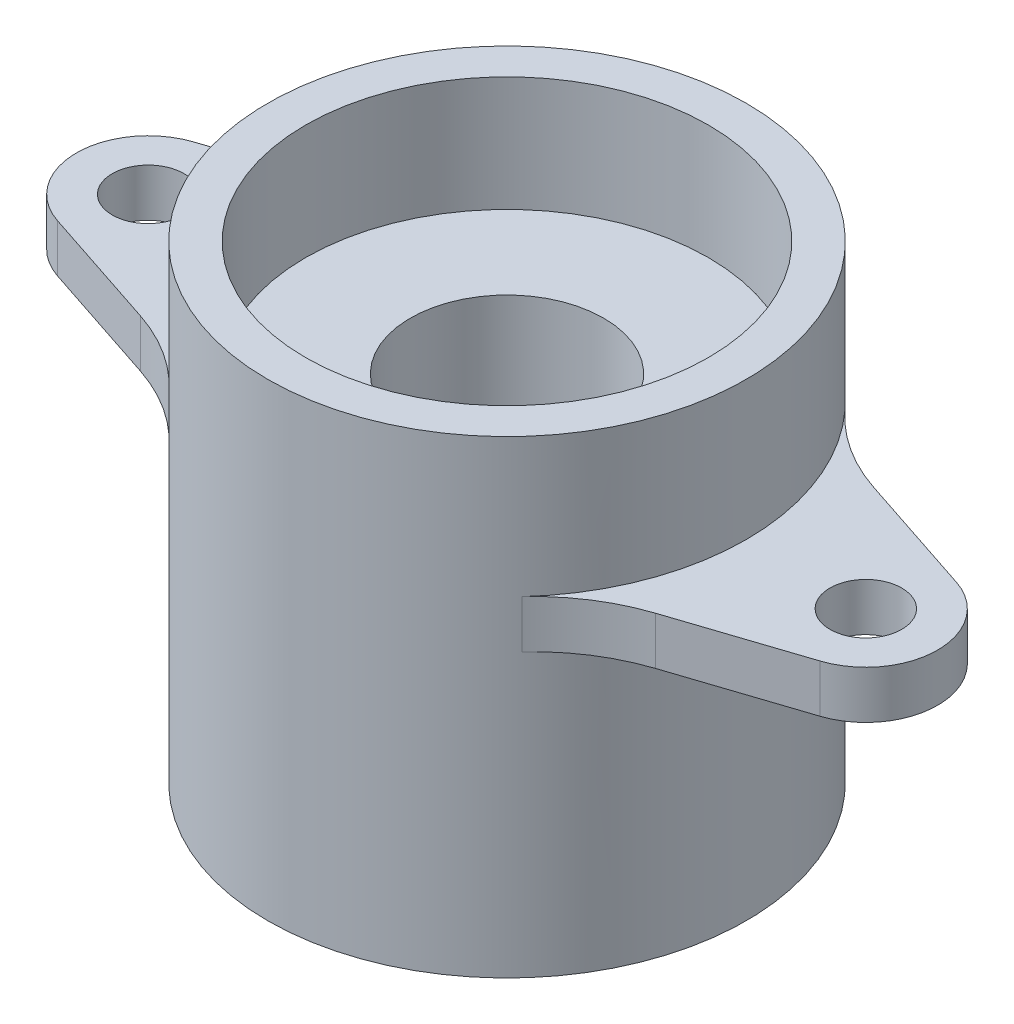
SolidWorks part; units mm, degrees
material "1060 Alloy"
ref_plane "Front Plane" through (0, 0, 0) normal (0, 0, 1) x (1, 0, 0)
ref_plane "Top Plane" through (0, 0, 0) normal (0, 1, 0) x (1, 0, 0)
ref_plane "Right Plane" through (0, 0, 0) normal (1, 0, 0) x (0, 0, -1)
sketch "Sketch1" plane through (0, 0, 0) normal (0, 0, 1) x (1, 0, 0)
  line L0 (21.05, 24.5) -> (25, 24.5)
  line L1 (21.05, 24.5) -> (21.05, 12.5)
  line L2 (21.05, 12.5) -> (10.1, 12.5)
  line L3 (10.1, 12.5) -> (10.1, -12.5)
  line L4 (25, 24.5) -> (25, -24.5)
  line L5 (25, -24.5) -> (21.05, -24.5)
  line L6 (21.05, -24.5) -> (21.05, -12.5)
  line L7 (21.05, -12.5) -> (10.1, -12.5)
  line L8 (0, 0) -> (0, 21.563) construction
  point P11 (10.1, 0)
  dimension "D1" = 12
  dimension "D2" = 12
  dimension "D3" = 21.05
  dimension "D4" = 10.1
  dimension "D5" = 25
  dimension "D6" = 3.95
revolve "Revolve1" add sketch "Sketch1" angle 360 about L8
sketch "Sketch2" plane through (0, 0, 0) normal (0, 1, 0) x (1, 0, 0)
  line L0 (-37.5, 0) -> (37.5, 0) construction
  line L1 (-39.8542, 7.1209) -> (-26.9111, 11.3999)
  line L2 (-39.8542, -7.1209) -> (-26.9111, -11.3999)
  line L3 (-18.4383, 16.8828) -> (-18.4383, -16.8828)
  line L4 (0, -25) -> (0, 25) construction
  line L5 (18.4383, 16.8828) -> (18.4383, -16.8828)
  line L6 (39.8542, -7.1209) -> (26.9111, -11.3999)
  line L7 (39.8542, 7.1209) -> (26.9111, 11.3999)
  circle A0 centre (-37.5, 0) radius 3.75
  arc A1 (-39.8542, 7.1209) -> (-39.8542, -7.1209) centre (-37.5, 0) ccw
  circle A2 centre (0, 0) radius 25 construction
  arc A3 (-18.4383, -16.8828) -> (-18.4383, 16.8828) centre (0, 0) ccw construction
  arc A4 (-26.9111, -11.3999) -> (-18.4383, -16.8828) centre (-33.1889, -30.3891) cw
  arc A5 (-26.9111, 11.3999) -> (-18.4383, 16.8828) centre (-33.1889, 30.3891) ccw
  arc A6 (26.9111, 11.3999) -> (18.4383, 16.8828) centre (33.1889, 30.3891) cw
  arc A7 (26.9111, -11.3999) -> (18.4383, -16.8828) centre (33.1889, -30.3891) ccw
  arc A8 (39.8542, 7.1209) -> (39.8542, -7.1209) centre (37.5, 0) cw
  circle A9 centre (37.5, 0) radius 3.75
  point P12 (0, 0)
  point P15 (-21.1699, -13.298)
  point P18 (-21.1699, 13.298)
  point P21 (0, 0)
  dimension "D1" = 15
  dimension "D2" = 7.5
  dimension "D3" = 75
  dimension "D4" = 20
extrude "Boss-Extrude1" add sketch "Sketch2" along normal blind 5 from offset 5
sketch "Sketch3" plane through (0, 0, 0) normal (1, 0, 0) x (0, 0, -1)
  line L0 (-25, 0) -> (25, 0)
  line L1 (25, -24.5) -> (25, 24.5) construction
  line L2 (-25, 24.5) -> (-25, -24.5) construction
sketch "Sketch4" plane through (0, 24.5, 0) normal (0, 1, 0) x (1, 0, 0)
  line L0 (-45, 0) -> (45, 0)
  arc A0 (-39.8542, 7.1209) -> (-39.8542, -7.1209) centre (-37.5, 0) ccw construction
  arc A1 (39.8542, -7.1209) -> (39.8542, 7.1209) centre (37.5, 0) ccw construction
